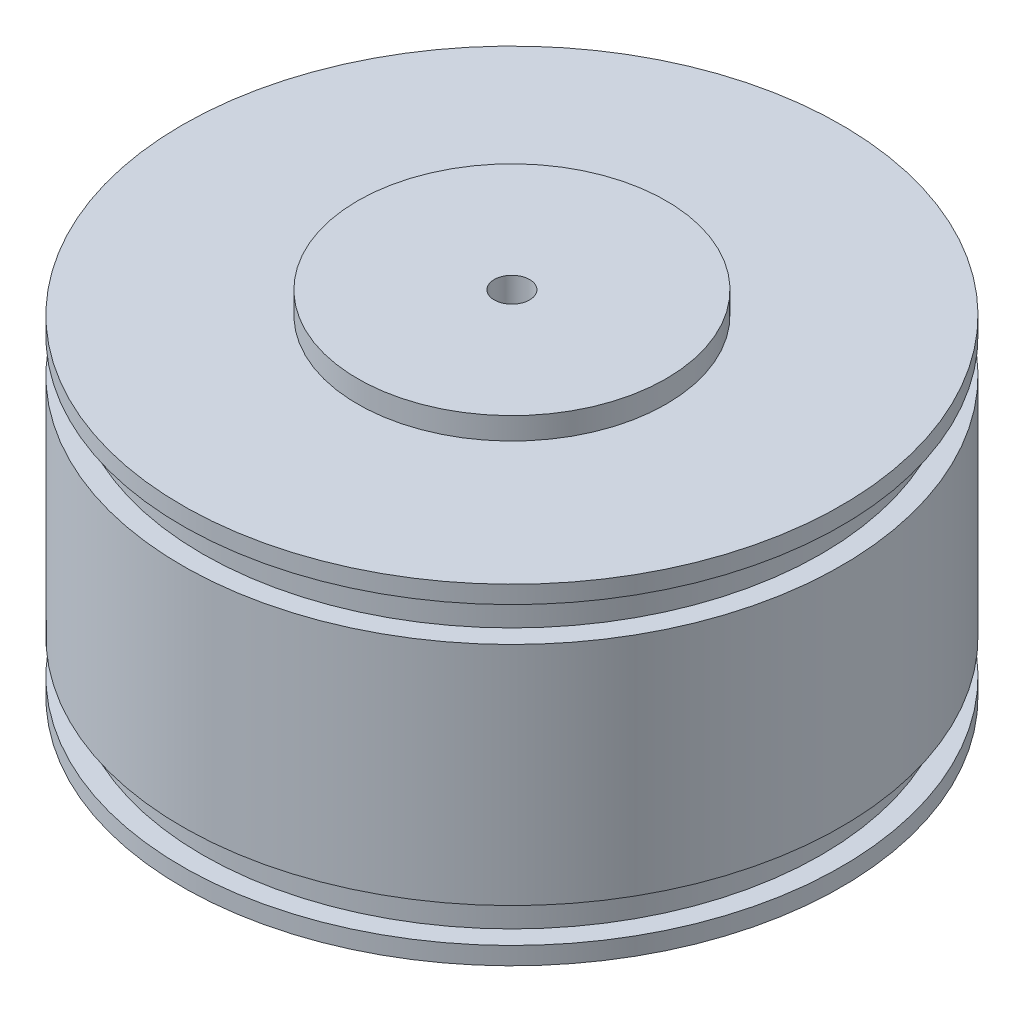
SolidWorks part; units mm, degrees
material "6061-T6 (SS)"
ref_plane "Front Plane" through (0, 0, 0) normal (0, 0, 1) x (1, 0, 0)
ref_plane "Top Plane" through (0, 0, 0) normal (0, 1, 0) x (1, 0, 0)
ref_plane "Right Plane" through (0, 0, 0) normal (1, 0, 0) x (0, 0, -1)
sketch "Sketch1" plane through (0, 0, 0) normal (0, 0, 1) x (1, 0, 0)
  line L0 (0, 38.9011) -> (0, -20.7245) construction
  line L1 (0, 0) -> (22.225, 0)
  line L2 (47.498, -3.175) -> (47.498, -5.715)
  line L3 (47.498, -50.8) -> (41.148, -50.8)
  line L4 (41.148, -50.8) -> (41.148, -12.7)
  line L5 (41.148, -12.7) -> (0, -12.7)
  line L6 (0, -12.7) -> (0, 0)
  line L7 (47.498, -10.6934) -> (47.498, -28.7782)
  line L8 (47.498, -48.26) -> (44.577, -48.26)
  line L10 (47.498, -43.2816) -> (44.577, -43.2816)
  line L11 (44.577, -48.26) -> (44.577, -43.2816)
  line L12 (47.498, -33.7566) -> (44.577, -33.7566) construction
  line L14 (47.498, -28.7782) -> (44.577, -28.7782) construction
  line L15 (44.577, -33.7566) -> (44.577, -28.7782) construction
  line L16 (47.498, -10.6934) -> (44.577, -10.6934)
  line L18 (47.498, -5.715) -> (44.577, -5.715)
  line L19 (44.577, -10.6934) -> (44.577, -5.715)
  line L20 (47.498, -33.7566) -> (47.498, -43.2816)
  line L21 (47.498, -48.26) -> (47.498, -50.8)
  line L22 (47.498, -28.7782) -> (47.498, -33.7566)
  line L23 (47.498, -3.175) -> (22.225, -3.175)
  line L24 (22.225, -3.175) -> (22.225, 0)
  dimension "D1" = 94.996
  dimension "D2" = 6.35
  dimension "D3" = 12.7
  dimension "D4" = 4.9784
  dimension "D5" = 2.921
  dimension "D6" = 2.54
  dimension "D7" = 9.525
  dimension "D8" = 44.45
  dimension "D9" = 50.8
  dimension "D10" = 3.175
  dimension "D11" = 2.54
revolve "Revolve1" add sketch "Sketch1" angle 360 about L0
hole_wizard "1/4-20 Tapped Hole1" positions "Sketch2" profile "Sketch3" tap size "1/4-20" standard "ANSI Inch"
sketch "Sketch2" plane through (0, 0, 0) normal (0, 1, 0) x (1, 0, 0)
  point P0 (0, 0)
sketch "Sketch3" plane through (0, 0, 0) normal (1, 0, 0) x (0, 0, 1)
  line L0 (0, 0) -> (0, 9.652)
  line L1 (0, 9.652) -> (2.5527, 8.1182)
  line L2 (2.5527, 8.1182) -> (2.5527, 0)
  line L5 (2.5527, 0) -> (0, 0)
  line L10 (0, 9.652) -> (-2.5527, 8.1182) construction
  line L11 (0, -6.35) -> (0, 107.95) construction
  dimension "Tap Drill Dia." = 5.1054
  dimension "Tap Drill Depth" = 9.652
  dimension "Drill Angle" = 118
cosmetic thread "Hole Thread1"
